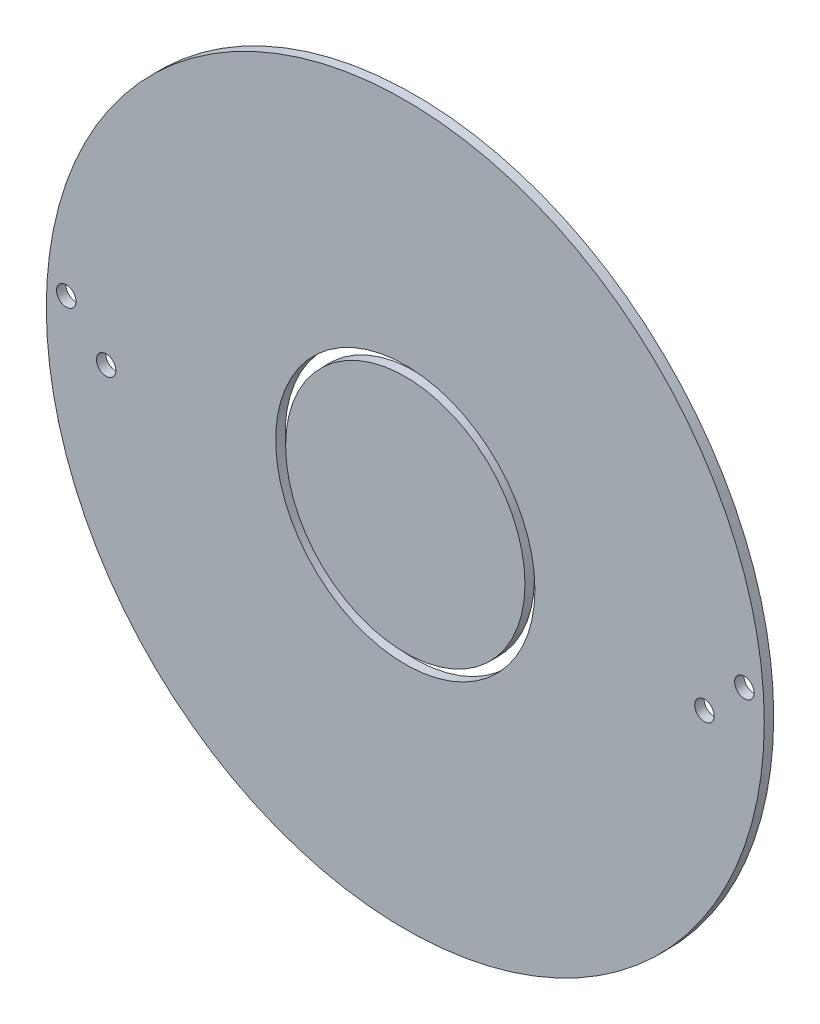
SolidWorks part; units mm, degrees
ref_plane "Front" through (0, 0, 0) normal (0, 0, 1) x (1, 0, 0)
ref_plane "Top" through (0, 0, 0) normal (0, 1, 0) x (1, 0, 0)
ref_plane "Right" through (0, 0, 0) normal (1, 0, 0) x (0, 0, -1)
sketch "Sketch1" plane through (0, 0, 0) normal (0, 0, 1) x (1, 0, 0)
  circle A0 centre (0, 0) radius 57.15
extrude "Extrude1" add sketch "Sketch1" along normal blind 1.5
sketch "Sketch2" plane through (0, 0, 1.5) normal (0, 0, 1) x (1, 0, 0)
  circle A0 centre (-53.975, 3.175) radius 1.55
  circle A1 centre (-47.625, -3.175) radius 1.55
  circle A2 centre (53.975, 3.175) radius 1.55
  circle A3 centre (47.625, -3.175) radius 1.55
extrude "Cut-Extrude1" cut sketch "Sketch2" against normal through all
sketch "Sketch3" plane through (0, 0, 1.5) normal (0, 0, 1) x (1, 0, 0)
  circle A0 centre (0, 0) radius 19.05
  circle A1 centre (0, 0) radius 20.6375
extrude "Cut-Extrude2" cut sketch "Sketch3" against normal through all
